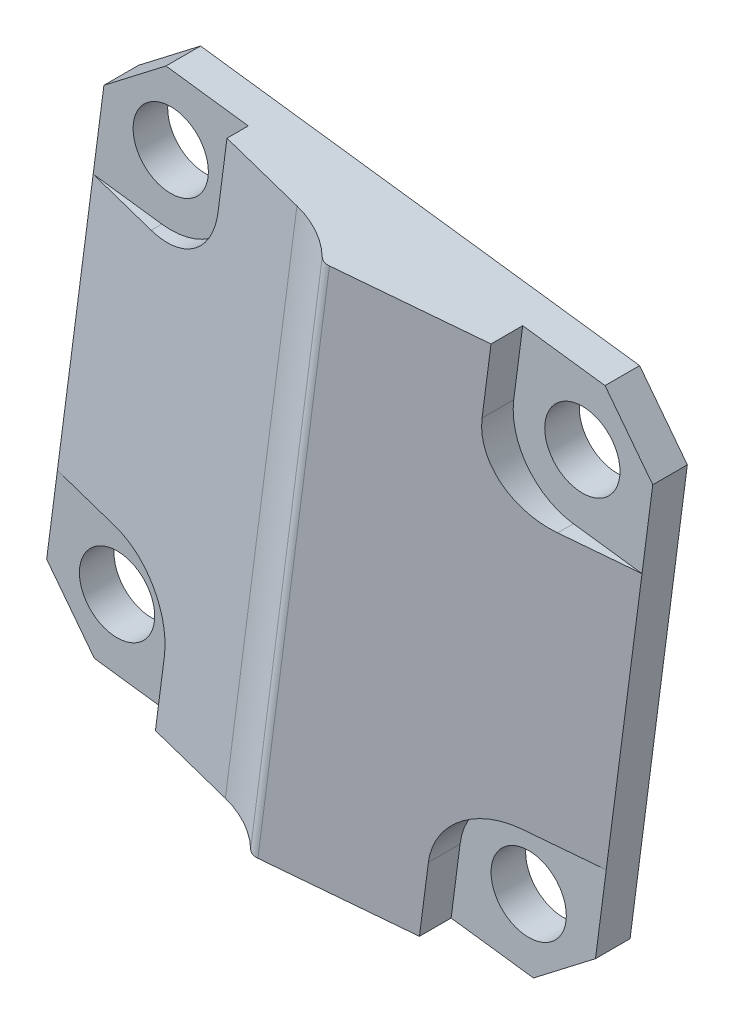
SolidWorks part; units mm, degrees
material "PET"
ref_plane "Front Plane" through (0, 0, 0) normal (0, 0, 1) x (1, 0, 0)
ref_plane "Top Plane" through (0, 0, 0) normal (0, 1, 0) x (1, 0, 0)
ref_plane "Right Plane" through (0, 0, 0) normal (1, 0, 0) x (0, 0, -1)
sketch "Reference" plane through (0, 0, 0) normal (0, 0, 1) x (1, 0, 0)
  line L2 (37.0142, -65.193) -> (37.0142, -133.528)
  line L3 (-111.7057, -139.0338) -> (-111.7057, -78.8372)
  line L4 (9.0014, -65.8409) -> (-3.9179, -104.9724)
  line L6 (-23.1411, -100.3781) -> (-17.3713, -56.1343)
  line L9 (-36.2613, -53.6709) -> (1.5188, -58.5978)
  arc A4 (37.0142, -133.528) -> (-111.7057, -139.0338) centre (-35.2286, -193.468) ccw
  point P1 (0, 0)
  point P13 (8.0286, -68.7874)
  point P26 (-17.3713, -56.1343)
  dimension "D1" = 93.8714
  dimension "D2" = 3.103
  dimension "D3" = 1.5188
  dimension "D4" = 8.0286
  dimension "D5" = 37.0142
  dimension "D6" = 3.9179
  dimension "D7" = 17.3713
  dimension "D8" = 23.1411
  dimension "D9" = 35.2286
  dimension "D10" = 53.6709
  dimension "D11" = 111.7057
  dimension "D14" = 65.193
  dimension "D15" = 78.8372
sketch "Sketch2" plane through (0, 0, 0) normal (0, 0, 1) x (1, 0, 0)
  line L0 (-37.3768, -111.3292) -> (-34.0922, -86.1425)
  line L1 (-37.3768, -111.3292) -> (-12.19, -114.6138)
  line L2 (-34.0922, -86.1425) -> (-8.9054, -89.4271)
  line L3 (-12.19, -114.6138) -> (-8.9054, -89.4271)
  line L4 (-37.3768, -111.3292) -> (-8.9054, -89.4271) construction
  line L5 (-34.0922, -86.1425) -> (-12.19, -114.6138) construction
  line L6 (-23.1411, -100.3781) -> (-17.3713, -56.1343) construction
  point P0 (-23.1411, -100.3781)
  point P1 (-23.1411, -100.3781)
  dimension "D1" = 25.4
  dimension "D2" = 25.4
extrude "Boss-Extrude1" add sketch "Sketch2" along normal blind 1.5875
sketch "Sketch3" plane through (-11.6161, -89.0736, 0) normal (0.1293, 0.9916, 0) x (0.9916, -0.1293, 0)
  line L0 (2.7336, -1.5875) -> (-22.6664, -1.5875) construction
  line L1 (2.7336, 0) -> (-22.6664, 0) construction
  line L2 (-11.5539, -4.5085) -> (-8.3789, -4.5085)
  line L3 (-9.9664, -4.5085) -> (-9.9664, 0) construction
  line L4 (-14.4749, -1.5875) -> (-5.4579, -1.5875)
  arc A0 (-14.4749, -1.5875) -> (-11.5539, -4.5085) centre (-14.4749, -4.5085) cw
  arc A1 (-5.4579, -1.5875) -> (-8.3789, -4.5085) centre (-5.4579, -4.5085) ccw
  point P16 (-9.9664, -1.5875)
  dimension "D1" = 4.5085
  dimension "D2" = 1.5875
extrude "Boss-Extrude2" [suppressed] add sketch "Sketch3" against normal up to surface (12.7 mm away)
sketch "Sketch4" plane through (-11.6161, -89.0736, 0) normal (0.1293, 0.9916, 0) x (0.9916, -0.1293, 0)
  line L0 (-22.6664, -1.5875) -> (-12.4842, -3.1552)
  line L1 (-9.9664, -4.4958) -> (2.7336, -1.5875)
  line L2 (2.7336, -1.5875) -> (-22.6664, -1.5875)
  line L3 (-13.1414, -7.424) -> (-12.4842, -3.1552) construction
  line L4 (-13.1414, -7.424) -> (-13.1414, 0) construction
  line L5 (2.7336, 0) -> (-22.6664, 0) construction
  arc A0 (-12.4842, -3.1552) -> (-9.9664, -4.4958) centre (-13.1414, -7.424) cw
  point P5 (0, 0)
  point P12 (-13.455, -6.7914)
  dimension "D1" = 4.4958
  dimension "D2" = 3.175
  dimension "D3" = 1.3406
extrude "Boss-Extrude3" add sketch "Sketch4" against normal up to surface (25.4 mm away) up to face at (-24.7834, -112.9715, 0.7937)
fillet "Fillet2" radius 0.508 1 edges at (-23.1411, -100.3781, 4.4958)
hole_wizard "#4 Clearance Hole1" positions "Sketch7" profile "Sketch8" hole size "#4" standard "ANSI Inch" end condition through all
sketch "Sketch7" plane through (0, 0, 0) normal (0, 0, -1) x (-1, 0, 0)
  line L0 (12.19, -114.6138) -> (8.9054, -89.4271) construction
  line L1 (8.9054, -89.4271) -> (34.0922, -86.1425) construction
  line L2 (9.316, -92.5754) -> (34.5027, -89.2908) construction
  line L4 (34.0922, -86.1425) -> (37.3768, -111.3292) construction
  line L6 (30.9438, -86.553) -> (34.2284, -111.7398) construction
  line L7 (37.3768, -111.3292) -> (12.19, -114.6138) construction
  line L9 (36.9662, -108.1808) -> (11.7795, -111.4654) construction
  line L11 (12.0538, -89.0165) -> (15.3384, -114.2032) construction
  point P0 (12.4643, -92.1648)
  point P2 (31.3544, -89.7014)
  point P4 (33.8178, -108.5914)
  point P6 (14.9278, -111.0549)
  point P44 (14.0588, -107.9663)
  dimension "D1" = 3.175
  dimension "D2" = 3.175
  dimension "D3" = 3.175
  dimension "D4" = 3.175
sketch "Sketch8" plane through (-12.4643, -92.1648, 0) normal (1, 0, 0) x (0, 1, 0)
  line L0 (0, 0) -> (0, 4.4453)
  line L1 (0, 4.4453) -> (1.7272, 4.4453)
  line L2 (1.7272, 4.4453) -> (1.7272, 0)
  line L5 (1.7272, 0) -> (0, 0)
  line L11 (0, -6.35) -> (0, 107.95) construction
  dimension "Thru Hole Dia." = 3.4544
  dimension "Thru Hole Depth" = 4.4453
sketch "Sketch9" plane through (0, 0, 0) normal (0, 0, -1) x (-1, 0, 0)
  line L0 (33.4073, -105.4431) -> (39.9741, -104.5867)
  line L1 (39.9741, -104.5867) -> (39.9741, -116.0838)
  line L3 (34.0922, -86.1425) -> (37.3768, -111.3292) construction
  line L4 (27.28, -112.6459) -> (37.3768, -111.3292) construction
  line L5 (30.6695, -109.002) -> (31.7125, -117.0002)
  line L6 (31.7125, -117.0002) -> (39.9741, -116.0838)
  line L7 (35.7345, -98.7358) -> (10.5477, -102.0204) construction
  line L8 (12.19, -114.6138) -> (8.9054, -89.4271) construction
  line L9 (21.4988, -87.7848) -> (24.7834, -112.9715) construction
  line L10 (8.9054, -89.4271) -> (34.0922, -86.1425) construction
  line L11 (37.3768, -111.3292) -> (12.19, -114.6138) construction
  line L12 (27.163, -82.1138) -> (35.3833, -80.8808)
  line L13 (28.2061, -90.1119) -> (27.163, -82.1138)
  line L14 (38.3318, -91.9933) -> (35.3833, -80.8808)
  line L15 (31.765, -92.8497) -> (38.3318, -91.9933)
  line L16 (12.8749, -95.3132) -> (6.3081, -96.1695)
  line L17 (6.3081, -96.1695) -> (6.3081, -84.6725)
  line L18 (15.6127, -91.7542) -> (14.5696, -83.7561)
  line L19 (14.5696, -83.7561) -> (6.3081, -84.6725)
  line L20 (19.1192, -118.6425) -> (10.8989, -119.8755)
  line L21 (18.0761, -110.6443) -> (19.1192, -118.6425)
  line L22 (7.9504, -108.7629) -> (10.8989, -119.8755)
  line L23 (14.5172, -107.9065) -> (7.9504, -108.7629)
  arc A0 (33.4073, -105.4431) -> (30.6695, -109.002) centre (33.8178, -108.5914) ccw
  arc A4 (31.765, -92.8497) -> (28.2061, -90.1119) centre (31.3544, -89.7014) cw
  arc A5 (12.8749, -95.3132) -> (15.6127, -91.7542) centre (12.4643, -92.1648) ccw
  arc A6 (14.5172, -107.9065) -> (18.0761, -110.6443) centre (14.9278, -111.0549) cw
extrude "Cut-Extrude3" cut sketch "Sketch9" along normal offset from surface (4.7625 mm away) 1.5875 from offset 6.35 up to face at (-14.1915, -92.1648, 0) offset against normal yes
chamfer "Chamfer1" distance 2.54 angle 45 4 edges at (-8.9054, -89.4271, 0.7937) (-12.19, -114.6138, 0.7937) (-37.3768, -111.3292, 0.7937) (-34.0922, -86.1425, 0.7937)
